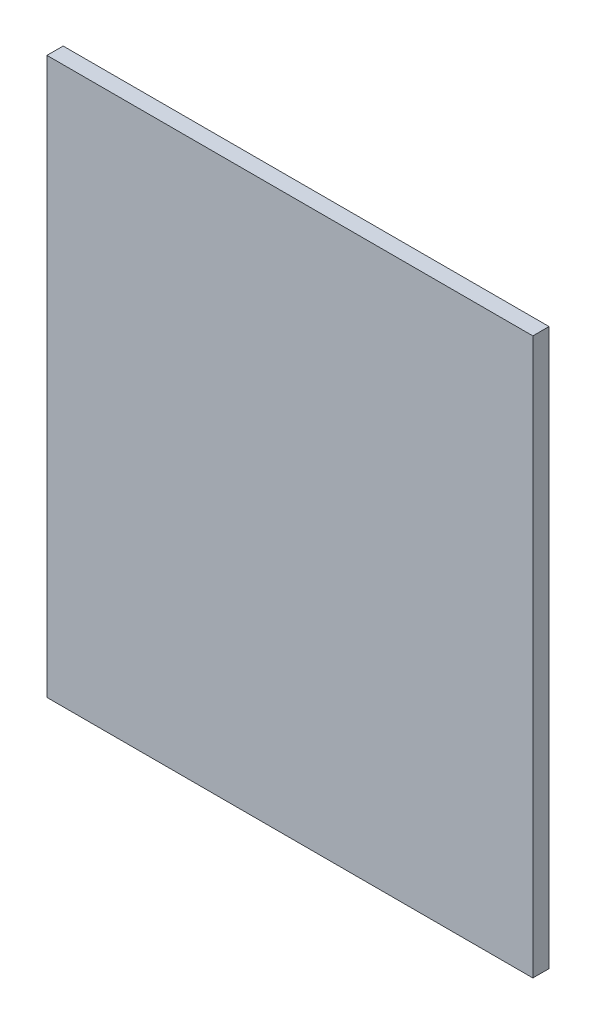
SolidWorks part; units mm, degrees
ref_plane "Plan de face" through (0, 0, 0) normal (0, 0, 1) x (1, 0, 0)
ref_plane "Plan de dessus" through (0, 0, 0) normal (0, 1, 0) x (1, 0, 0)
ref_plane "Plan de droite" through (0, 0, 0) normal (1, 0, 0) x (0, 0, -1)
sketch "Esquisse1" plane through (0, 0, 0) normal (0, 0, 1) x (1, 0, 0)
  line L1 (0, 0) -> (-180, 0)
  line L2 (0, 0) -> (0, 206)
  line L3 (0, 206) -> (-180, 206)
  line L4 (-180, 0) -> (-180, 206)
  dimension "D1" = 206
  dimension "D2" = 180
extrude "Boss.-Extru.1" add sketch "Esquisse1" along normal blind 6
